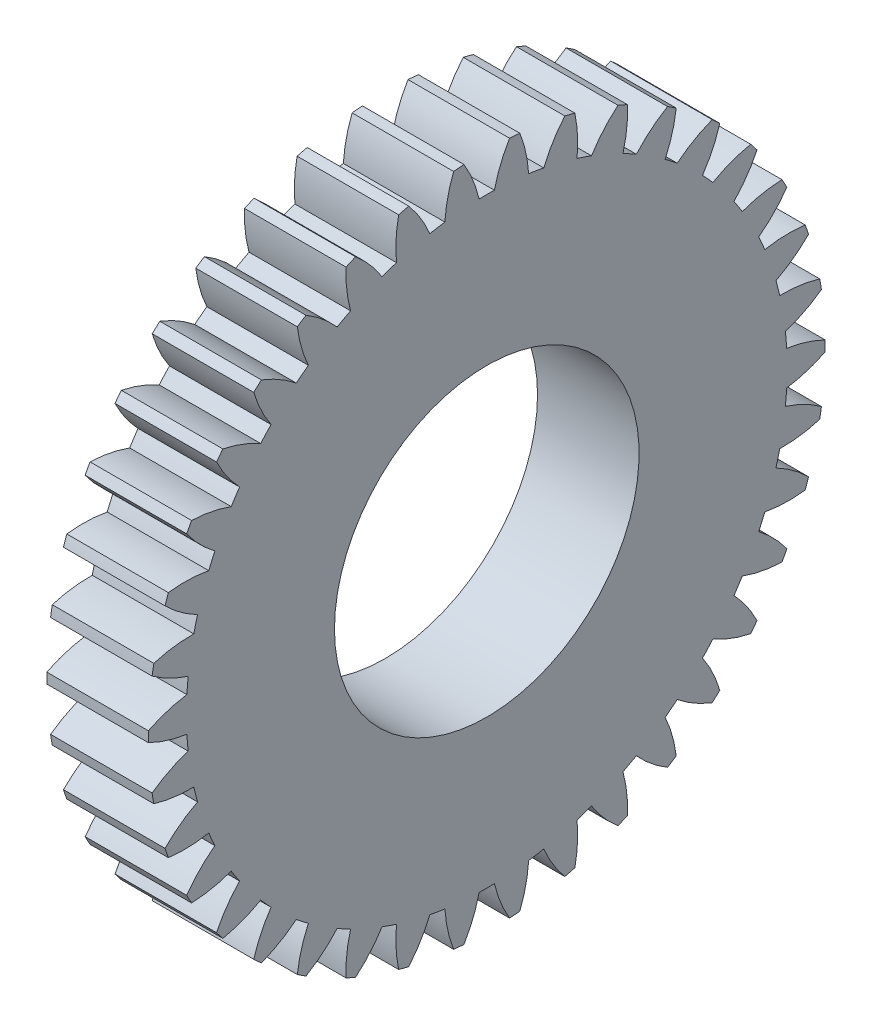
SolidWorks part; units mm, degrees
ref_plane "Plane1" through (0, 0, 0) normal (0, 0, 1) x (1, 0, 0)
ref_plane "Plane2" through (0, 0, 0) normal (0, 1, 0) x (1, 0, 0)
ref_plane "Plane3" through (0, 0, 0) normal (1, 0, 0) x (0, 0, -1)
sketch "HoldingSke" plane through (0, 0, 0) normal (0, 1, 0) x (1, 0, 0)
  line L0 (0, 0) -> (1.576, -1.2313)
  line L1 (-15, 0) -> (100, 0) construction
  line L2 (0, 0) -> (-2.1039, 2.3779)
  line L3 (0, 0) -> (-11.863, 4.5341)
  line L4 (0, 0) -> (6.8053, 5.3169)
  line L5 (0, 0) -> (-46.8476, -17.4728)
  line L6 (0, 0) -> (-2.4869, -1.6779)
  line L7 (-2.1039, 2.3779) -> (8.6586, 51.2059)
  line L8 (-76.2, 54.61) -> (-74.8, 54.61)
  line L9 (-71.009, 38.7566) -> (-53.1078, 45.2721)
  line L10 (-76.2, 71.12) -> (104.1128, 71.12)
  line L11 (0, 0) -> (-3, 0)
  line L12 (-76.2, 101.6) -> (-76.181, 101.6)
  line L13 (24.9733, 27.94) -> (52.9518, 28.4284)
  line L14 (24.9733, 27.94) -> (24.9743, 27.94)
  line L15 (24.9733, 27.94) -> (100.4006, 29.5858)
  line L16 (-63.627, -0.5) -> (-12.827, -0.5)
  circle A0 centre (0, 0) radius 4.5
  circle A1 centre (0, 0) radius 8.874
  circle A2 centre (0, 0) radius 37.5
  circle A3 centre (0, 0) radius 4.5
  dimension "MHD" = 17.748
  dimension "Hub_dia" = 75
  dimension "Bore" = 9
  dimension "MBD" = 9
  dimension "Num_teeth" = 38
  dimension "Pitch" = 2
  dimension "Overall_len" = 50
  dimension "Show_teeth" = 38
  dimension "Thickness" = 3
  dimension "OAL" = 50.0001
  dimension "T_dim" = 1.4
  dimension "Ap" = 20
  dimension "H" = 19.05
  dimension "Pitch_radius" = 180.3128
  dimension "Width" = 3
  dimension "Backlash" = 0.019
  dimension "Addendum_fac" = 1
  dimension "Dedendum_fac" = 1.25
  dimension "Clearance_fac" = 0.25
  dimension "Dedendum_add" = 0.001
  dimension "Module" = 0.5
sketch "BasProSke" plane through (0, 0, 0) normal (0, 1, 0) x (1, 0, 0)
  line L0 (-10, 0) -> (60, 0) construction
  line L1 (0, 0) -> (0, 10)
  line L2 (0, 0) -> (3, 0)
  line L3 (3, 0) -> (3, 10)
  line L4 (3, 10) -> (0, 10)
  dimension "Thickness" = 3
  dimension "Diameter" = 20
revolve "Base-Revolve" add sketch "BasProSke" angle 360 about L0
sketch "TooCutSke" plane through (0, 0, 0) normal (1, 0, 0) x (0, 0, -1)
  line L1 (0, 0) -> (0, 107) construction
  line L2 (0, 0) -> (-0.4258, 9.4905) construction
  line L3 (0, 0) -> (-1.5679, 18.9216) construction
  line L4 (-0.4258, 9.4905) -> (-0.7839, 9.4608) construction
  arc A0 (0.2256, 8.8711) -> (-0.2256, 8.8711) centre (0, 0) ccw
  arc A1 (0.6882, 10.0018) -> (-0.6882, 10.0018) centre (0, 0) ccw
  circle A2 centre (0, 0) radius 9.5 construction
  circle A3 centre (0, 0) radius 8.9271 construction
  arc A4 (-0.2256, 8.8711) -> (-0.6882, 10.0018) centre (-3.9283, 8.0163) ccw
  arc A5 (0.6882, 10.0018) -> (0.2256, 8.8711) centre (3.9283, 8.0163) ccw
  dimension "Root_dia" = 17.748
  dimension "Overcut_dia" = 20.0508
  dimension "Pitch_dia" = 19
  dimension "Base_dia" = 17.8542
  dimension "Flank_rad" = 3.8
  dimension "Half_ang" = 4.737
  dimension "Half_CT" = 0.3593
extrude "ToothCut" cut sketch "TooCutSke" along normal through all
fillet "Breaks" [suppressed] radius 0.01
fillet "RootFillets" [suppressed] radius 0.126
pattern_circular "TeethCuts" count 38 every 9.474 about axis through (-10, 0, 0) along (1, 0, 0) of "ToothCut", "RootFillets", "Breaks"
sketch "HubNeaOneSke" plane through (0, 0, 0) normal (-1, 0, 0) x (0, 0, 1)
  circle A0 centre (0, 0) radius 8.874
  dimension "Diameter" = 17.748
extrude "HubNearOne" [suppressed] add sketch "HubNeaOneSke" along normal blind 47.0001
sketch "HubNeaBotSke" plane through (0, 0, 0) normal (-1, 0, 0) x (0, 0, 1)
  circle A0 centre (0, 0) radius 8.874
  dimension "Diameter" = 17.748
extrude "HubNearBoth" [suppressed] add sketch "HubNeaBotSke" along normal blind 23.5
ref_plane "FarPln" through (3, 0, 0) normal (1, 0, 0) x (0, 0, -1)
sketch "HubFarSke" plane through (3, 0, 0) normal (1, 0, 0) x (0, 0, -1)
  circle A0 centre (0, 0) radius 8.874
  dimension "Diameter" = 17.748
extrude "HubFar" [suppressed] add sketch "HubFarSke" along normal blind 23.5
sketch "BorSke" plane through (0, 0, 0) normal (1, 0, 0) x (0, 0, -1)
  circle A0 centre (0, 0) radius 4.5
  dimension "Diameter" = 9
extrude "Bore" cut sketch "BorSke" along normal mid plane 100.0001
sketch "KeySke" plane through (0, 0, 0) normal (1, 0, 0) x (0, 0, -1)
  line L0 (-1.5, 0) -> (-1.5, 5.9)
  line L1 (-1.5, 5.9) -> (1.5, 5.9)
  line L2 (1.5, 5.9) -> (1.5, 0)
  line L3 (0, 0) -> (0, 34) construction
  line L4 (-1.5, 0) -> (1.5, 0)
  dimension "Width" = 3
  dimension "Offset" = 5.9
extrude "Keyway" [suppressed] cut sketch "KeySke" along normal mid plane 100.0001
pattern_circular "Keyway2" [suppressed] count 2 every 90 about axis through (-10, 0, 0) along (1, 0, 0)
equation "' \"Module@HoldingSke\" = 6.35"
equation "' \"Num_teeth@HoldingSke\" = 12"
equation "' \"Ap@HoldingSke\" =  20"
equation "' \"Ap@HoldingSke\" = 20"
equation "' \"Width@HoldingSke\" = 0.5 * 25.4"
equation "' \"Hub_dia@HoldingSke\"= 1 * 25.4"
equation "' \"Hub_dia@HoldingSke\" = 1 * 25.4"
equation "' \"Overall_len@HoldingSke\" = 1.0 * 25.4"
equation "' \"Bore@HoldingSke\" = 0.75 * 25.4"
equation "' \"T_dim@HoldingSke\" = 0.1 * 25.4"
equation "' \"Width@KeySke\" = 0.25 * 25.4"
equation "' \"Show_teeth@HoldingSke\" = 13"
equation "' \"Backlash@HoldingSke\" = 0.009 * 25.4"
equation "' \"Addendum_fac@HoldingSke\" = 1.0"
equation "' \"Dedendum_fac@HoldingSke\" = 1.25"
equation "' \"Dedendum_add@HoldingSke\" = 0.00005 * 25.4"
equation "' \"Clearance_fac@HoldingSke\" = 0.25"
equation "\"Pitch@HoldingSke\" = 1 / \"Module@HoldingSke\""
equation "\"Overcut_dia@TooCutSke\" = (\"Num_teeth@HoldingSke\" + 2 * \"Addendum_fac@HoldingSke\") / \"Pitch@HoldingSke\" + 0.002 * 25.4"
equation "\"Pitch_dia@TooCutSke\" = \"Num_teeth@HoldingSke\" / \"Pitch@HoldingSke\""
equation "\"Base_dia@TooCutSke\" = \"Num_teeth@HoldingSke\" / \"Pitch@HoldingSke\" * cos((\"Ap@HoldingSke\"  * 3.14159265 / 180))"
equation "\"Root_dia@TooCutSke\" = (\"Num_teeth@HoldingSke\" + 2) / \"Pitch@HoldingSke\" - 2 * (\"Addendum_fac@HoldingSke\" + \"Dedendum_fac@HoldingSke\") / \"Pitch@HoldingSke\" - \"Dedendum_add@HoldingSke\" * 2"
equation "\"Half_ang@TooCutSke\" = 180 / \"Num_teeth@HoldingSke\""
equation "\"Half_CT@TooCutSke\" = \"Num_teeth@HoldingSke\" / \"Pitch@HoldingSke\" * sin((3.14159265 / 2 / \"Num_teeth@HoldingSke\")) / 2 - 7 * \"Backlash@HoldingSke\" / 4"
equation "\"Flank_rad@TooCutSke\" = \"Num_teeth@HoldingSke\" / \"Pitch@HoldingSke\" / 5"
equation "\"Radius@RootFillets\" = \"Clearance_fac@HoldingSke\" / \"Pitch@HoldingSke\" + \"Dedendum_add@HoldingSke\""
equation "\"Break_rad@Breaks\" = 0.02 / \"Pitch@HoldingSke\""
equation "\"Thickness@HoldingSke\" = \"Width@HoldingSke\""
equation "\"OAL@HoldingSke\" = \"Thickness@HoldingSke\""
equation "\"MHD@HoldingSke\" = (\"Num_teeth@HoldingSke\" + 2) / \"Pitch@HoldingSke\" - 2 * (\"Addendum_fac@HoldingSke\" + \"Dedendum_fac@HoldingSke\")  / \"Pitch@HoldingSke\" - \"Dedendum_add@HoldingSke\" * 2"
equation "\"MBD@HoldingSke\" = (\"Num_teeth@HoldingSke\" + 2) / \"Pitch@HoldingSke\" - 2 * (\"Addendum_fac@HoldingSke\" + \"Dedendum_fac@HoldingSke\")  / \"Pitch@HoldingSke\" - \"Dedendum_add@HoldingSke\" * 2 - 0.002 * 25.4"
equation "\"MHD@HoldingSke\" = ((sgn( \"MHD@HoldingSke\" - \"Hub_dia@HoldingSke\" )-1)*( \"MHD@HoldingSke\" - \"Hub_dia@HoldingSke\" ))/-2+ \"Hub_dia@HoldingSke\""
equation "\"MBD@HoldingSke\" = ((sgn( \"MBD@HoldingSke\" - \"Bore@HoldingSke\" )-1)*( \"MBD@HoldingSke\" - \"Bore@HoldingSke\" ))/-2+ \"Bore@HoldingSke\""
equation "\"OAL@HoldingSke\" = ((sgn( \"OAL@HoldingSke\" - \"Overall_len@HoldingSke\" )+1)*( \"OAL@HoldingSke\" - \"Overall_len@HoldingSke\" ))/2 + \"Overall_len@HoldingSke\" + 0.000002 * 25.4"
equation "\"Num_teeth@TeethCuts\" = int( \"Show_teeth@HoldingSke\" ) + 1"
equation "\"Num_teeth@TeethCuts\" = ((sgn( \"Num_teeth@TeethCuts\" - \"Num_teeth@HoldingSke\" )-1)*( \"Num_teeth@TeethCuts\" - \"Num_teeth@HoldingSke\" ))/-2+ \"Num_teeth@HoldingSke\""
equation "\"Num_teeth@TeethCuts\" = ((sgn( \"Num_teeth@TeethCuts\" - 2.0)+1)*( \"Num_teeth@TeethCuts\" - 2.0))/2 +2.0"
equation "\"Angle@TeethCuts\" = 360.0 / \"Num_teeth@HoldingSke\""
equation "\"Diameter@BasProSke\" = (\"Num_teeth@HoldingSke\" + 2 * \"Addendum_fac@HoldingSke\") / \"Pitch@HoldingSke\""
equation "\"Thickness@BasProSke\"  = \"Thickness@HoldingSke\""
equation "' \"Fillet_rad@BasProSke\" =  \"Thickness@HoldingSke\" * 0.05"
equation "' \"Fillet_rad@BasProSke\" = \"Thickness@HoldingSke\" * 0.05"
equation "\"MHD@HoldingSke\" = ((sgn( \"MHD@HoldingSke\" - \"Root_dia@TooCutSke\" )-1)*( \"MHD@HoldingSke\" - \"Root_dia@TooCutSke\" ))/-2+ \"Root_dia@TooCutSke\""
equation "\"Diameter@HubNeaOneSke\" = \"MHD@HoldingSke\""
equation "\"Length@HubNearOne\" = \"OAL@HoldingSke\" - \"Thickness@BasProSke\""
equation "\"Diameter@HubNeaBotSke\" = \"MHD@HoldingSke\""
equation "\"Length@HubNearBoth\" = ( \"OAL@HoldingSke\" - \"Thickness@BasProSke\" ) / 2.0"
equation "\"Thickness@FarPln\" = \"Thickness@BasProSke\""
equation "\"Diameter@HubFarSke\" = \"MHD@HoldingSke\""
equation "\"Length@HubFar\" = ( \"OAL@HoldingSke\" - \"Thickness@BasProSke\" ) / 2.0"
equation "\"Diameter@BorSke\" = \"MBD@HoldingSke\""
equation "\"D1@Bore\" = \"OAL@HoldingSke\" * 2.0"
equation "\"D1@Keyway\" = \"OAL@HoldingSke\" * 2.0"
equation "\"Offset@KeySke\" = \"T_dim@HoldingSke\" + \"MBD@HoldingSke\" / 2.0"
